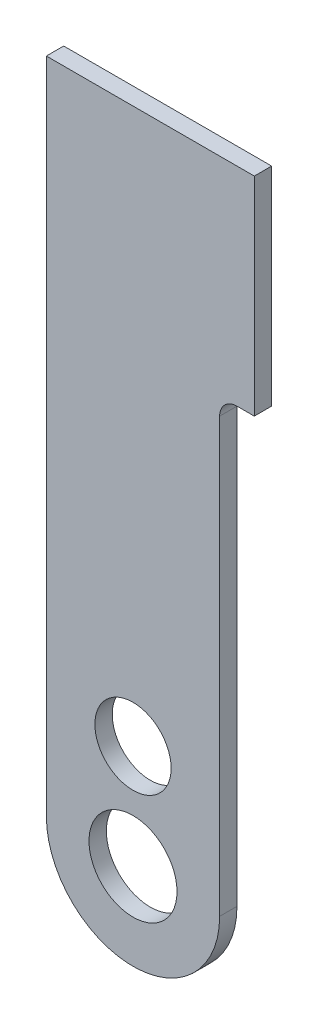
SolidWorks part; units mm, degrees
material "6061-T6 (SS)"
ref_plane "Front Plane" through (0, 0, 0) normal (0, 0, 1) x (1, 0, 0)
ref_plane "Top Plane" through (0, 0, 0) normal (0, 1, 0) x (1, 0, 0)
ref_plane "Right Plane" through (0, 0, 0) normal (1, 0, 0) x (0, 0, -1)
sketch "Sketch1" plane through (0, 0, 0) normal (0, 0, 1) x (1, 0, 0)
  circle A0 centre (0, -30) radius 25
  dimension "D1" = 50
  dimension "D2" = 30
extrude "Boss-Extrude1" add sketch "Sketch1" along normal mid plane 5 contours A0
sketch "Sketch3" plane through (0, 0, 0) normal (0, 0, 1) x (1, 0, 0)
  line L1 (-25, -30) -> (25, -30)
  line L2 (-25, -30) -> (-25, 160)
  line L3 (-25, 160) -> (25, 160)
  line L4 (25, -30) -> (25, 160)
  dimension "D1" = 25
  dimension "D2" = 25
  dimension "D3" = 30
  dimension "D4" = 190
extrude "Boss-Extrude2" add sketch "Sketch3" along normal mid plane 5
sketch "Sketch4" plane through (0, 0, 0) normal (0, 0, 1) x (1, 0, 0)
  line L1 (25, 160) -> (35, 160)
  line L2 (25, 160) -> (25, 100)
  line L3 (25, 100) -> (35, 100)
  line L4 (35, 160) -> (35, 100)
  dimension "D1" = 25
  dimension "D2" = 100
  dimension "D3" = 10
  dimension "D4" = 60
extrude "Boss-Extrude3" add sketch "Sketch4" along normal mid plane 5
sketch "Sketch7" plane through (0, 0, 0) normal (0, 0, 1) x (1, 0, 0)
  circle A0 centre (0, 0) radius 11
  circle A1 centre (0, -30) radius 12.7
  dimension "D1" = 22
  dimension "D2" = 25.4
  dimension "D3" = 30
extrude "Cut-Extrude2" cut sketch "Sketch7" against normal through all and the other way through all
fillet "Fillet1" radius 5 1 edges at (25, 100, 0)
